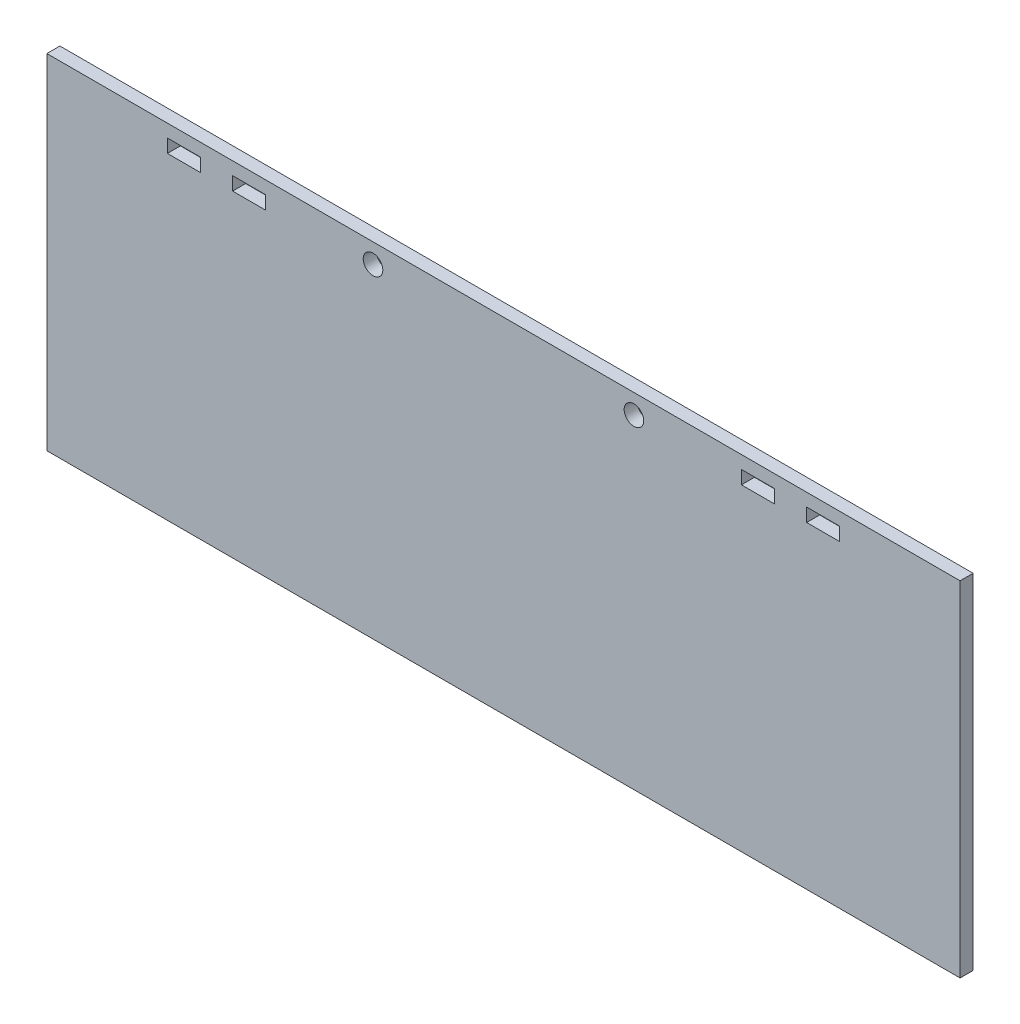
SolidWorks part; units mm, degrees
ref_plane "前视基准面" through (0, 0, 0) normal (0, 0, 1) x (1, 0, 0)
ref_plane "上视基准面" through (0, 0, 0) normal (0, 1, 0) x (1, 0, 0)
ref_plane "右视基准面" through (0, 0, 0) normal (1, 0, 0) x (0, 0, -1)
sketch "草图1" plane through (0, 0, 0) normal (0, 0, 1) x (1, 0, 0)
  line L4 (54.275, -1.025) -> (54.275, 1.975) construction
  line L5 (54.275, 1.975) -> (-15.725, 1.975)
  line L11 (12.75, 0) -> (17.8, 0)
  line L12 (12.75, 0) -> (12.75, -2.05)
  line L13 (12.75, -2.05) -> (17.8, -2.05)
  line L31 (17.8, 0) -> (17.8, -2.05)
  line L32 (12.75, 0) -> (17.8, -2.05) construction
  line L33 (12.75, -2.05) -> (17.8, 0) construction
  line L36 (2.75, 0) -> (7.8, 0)
  line L37 (2.75, 0) -> (2.75, -2.05)
  line L38 (2.75, -2.05) -> (7.8, -2.05)
  line L39 (7.8, 0) -> (7.8, -2.05)
  line L40 (2.75, 0) -> (7.8, -2.05) construction
  line L41 (2.75, -2.05) -> (7.8, 0) construction
  line L42 (34.275, -1.025) -> (74.275, -1.025) construction
  line L43 (54.275, -1.025) -> (54.275, -5.3567) construction
  line L44 (105.8, -2.05) -> (100.75, 0) construction
  line L45 (105.8, 0) -> (100.75, -2.05) construction
  line L46 (95.8, -2.05) -> (90.75, 0) construction
  line L47 (95.8, 0) -> (90.75, -2.05) construction
  line L48 (54.275, 1.975) -> (124.275, 1.975)
  line L49 (124.275, 1.975) -> (124.275, -50.7609)
  line L50 (100.75, 0) -> (100.75, -2.05)
  line L51 (105.8, -2.05) -> (100.75, -2.05)
  line L52 (105.8, 0) -> (105.8, -2.05)
  line L53 (105.8, 0) -> (100.75, 0)
  line L54 (90.75, 0) -> (90.75, -2.05)
  line L55 (95.8, -2.05) -> (90.75, -2.05)
  line L56 (95.8, 0) -> (95.8, -2.05)
  line L57 (95.8, 0) -> (90.75, 0)
  line L60 (124.275, -50.7609) -> (-15.725, -50.7609)
  line L61 (-15.725, -50.7609) -> (-15.725, 1.975)
  circle A0 centre (34.275, -1.025) radius 1.5
  circle A2 centre (74.275, -1.025) radius 1.5
extrude "凸台-拉伸1" add sketch "草图1" along normal blind 2
